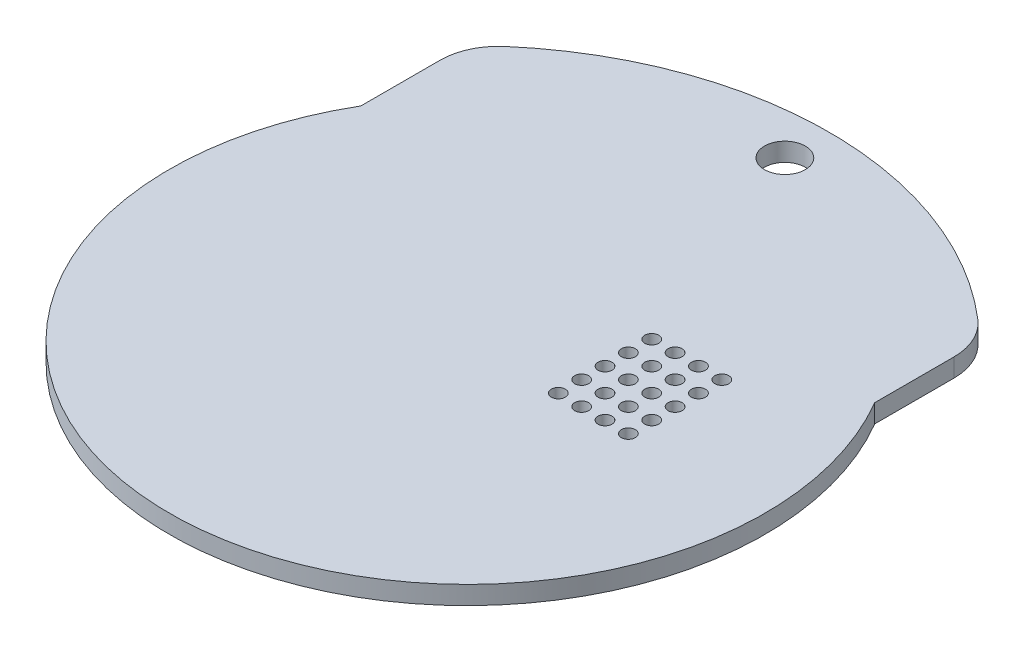
SolidWorks part; units mm, degrees
material "Acrylic (Medium-high impact)"
ref_plane "Front Plane" through (0, 0, 0) normal (0, 0, 1) x (1, 0, 0)
ref_plane "Top Plane" through (0, 0, 0) normal (0, 1, 0) x (1, 0, 0)
ref_plane "Right Plane" through (0, 0, 0) normal (1, 0, 0) x (0, 0, -1)
sketch "Sketch1" plane through (0, 0, 0) normal (0, 1, 0) x (1, 0, 0)
  line L0 (-27.94, 16.3751) -> (-27.94, 27.7372)
  line L1 (27.94, 16.3751) -> (27.94, 27.7372)
  circle A0 centre (0, 0) radius 32.385
  arc A1 (-27.94, 27.7372) -> (27.94, 27.7372) centre (0, 0) cw
  dimension "D3" = 64.77
  dimension "D4" = 39.37
  dimension "D1" = 27.94
  dimension "D2" = 55.88
extrude "Boss-Extrude1" add sketch "Sketch1" along normal blind 2 contours A0 | A1 L0 A0 L1
fillet "Fillet1" radius 6.35 2 edges at (27.94, 1, -27.7372) (-27.94, 1, -27.7372)
sketch "Sketch2" plane through (0, 2, 0) normal (0, 1, 0) x (1, 0, 0)
  arc A0 (-27.94, 16.3751) -> (27.94, 16.3751) centre (0, 0) ccw construction
  circle A2 centre (0, 34.544) radius 2.2225
  dimension "D1" = 34.544
  dimension "D7" = 4.445
extrude "Cut-Extrude1" cut sketch "Sketch2" against normal through all
sketch "Sketch5" plane through (0, 2, 0) normal (0, 1, 0) x (1, 0, 0)
  line L1 (9.8425, 10.2235) -> (17.4625, 10.2235)
  line L2 (9.8425, 10.2235) -> (9.8425, 0.0635)
  line L3 (9.8425, 0.0635) -> (17.4625, 0.0635)
  line L4 (17.4625, 10.2235) -> (17.4625, 0.0635)
  circle A0 centre (9.8425, 10.2235) radius 0.762
  circle A1 centre (12.3825, 10.2235) radius 0.762
  circle A2 centre (14.9225, 10.2235) radius 0.762
  circle A3 centre (17.4625, 10.2235) radius 0.762
  circle A4 centre (9.8425, 7.6835) radius 0.762
  circle A5 centre (12.3825, 7.6835) radius 0.762
  circle A6 centre (14.9225, 7.6835) radius 0.762
  circle A7 centre (17.4625, 7.6835) radius 0.762
  circle A8 centre (9.8425, 5.1435) radius 0.762
  circle A9 centre (12.3825, 5.1435) radius 0.762
  circle A10 centre (14.9225, 5.1435) radius 0.762
  circle A11 centre (17.4625, 5.1435) radius 0.762
  circle A12 centre (9.8425, 2.6035) radius 0.762
  circle A13 centre (12.3825, 2.6035) radius 0.762
  circle A14 centre (14.9225, 2.6035) radius 0.762
  circle A15 centre (17.4625, 2.6035) radius 0.762
  circle A16 centre (9.8425, 0.0635) radius 0.762
  circle A17 centre (12.3825, 0.0635) radius 0.762
  circle A18 centre (14.9225, 0.0635) radius 0.762
  circle A19 centre (17.4625, 0.0635) radius 0.762
  point P4 (13.6525, 5.1435)
  dimension "D7" = 4
  dimension "D1" = 13.6525
  dimension "D2" = 5.1435
  dimension "D3" = 3.81
  dimension "D4" = 3.81
  dimension "D5" = 5.08
  dimension "D6" = 5.08
  dimension "D8" = 5
extrude "Cut-Extrude2" cut sketch "Sketch5" against normal through all contours A0 | A1 | A2 | A3 | A4 | A5 | A6 | A7 | A8 | A9 | A10 | A11 | A15 | A14 | A13 | A12 | A16 | A17 | A18 | A19
